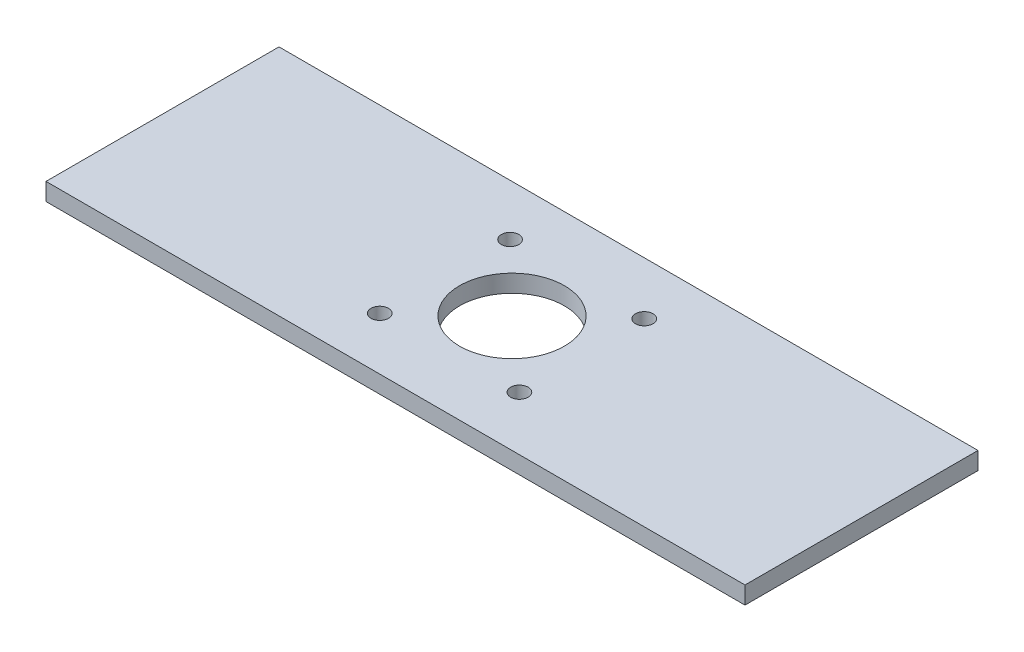
SolidWorks part; units mm, degrees
ref_plane "Front Plane" through (0, 0, 0) normal (0, 0, 1) x (1, 0, 0)
ref_plane "Top Plane" through (0, 0, 0) normal (0, 1, 0) x (1, 0, 0)
ref_plane "Right Plane" through (0, 0, 0) normal (1, 0, 0) x (0, 0, -1)
sketch "Sketch1" plane through (0, 0, 0) normal (0, 1, 0) x (1, 0, 0)
  line L1 (-95.25, -31.75) -> (95.25, -31.75)
  line L2 (-95.25, -31.75) -> (-95.25, 31.75)
  line L3 (-95.25, 31.75) -> (95.25, 31.75)
  line L4 (95.25, -31.75) -> (95.25, 31.75)
  line L5 (-95.25, -31.75) -> (95.25, 31.75) construction
  line L6 (-95.25, 31.75) -> (95.25, -31.75) construction
  point P0 (0, 0)
  dimension "D1" = 190.5
  dimension "D2" = 63.5
extrude "Boss-Extrude1" add sketch "Sketch1" along normal blind 4.7625
sketch "Sketch2" plane through (0, 4.7625, 0) normal (0, 1, 0) x (1, 0, 0)
  line L0 (-31.75, -31.75) -> (-31.75, 31.75)
  line L1 (-95.25, -31.75) -> (95.25, -31.75) construction
  line L2 (95.25, 31.75) -> (-95.25, 31.75) construction
  line L3 (-95.25, 31.75) -> (-95.25, -31.75) construction
  line L4 (31.75, 31.75) -> (31.75, -31.75)
  line L5 (95.25, -31.75) -> (95.25, 31.75) construction
  dimension "D1" = 63.5
  dimension "D2" = 63.5
sketch "Sketch3" plane through (0, 4.7625, 0) normal (0, 1, 0) x (1, 0, 0)
  circle A0 centre (0, 0) radius 14.2875
  dimension "D1" = 28.575
extrude "Cut-Extrude1" cut sketch "Sketch3" against normal through all
hole_wizard "3/16 (0.1875) Diameter Hole1" positions "Sketch4" profile "Sketch5" hole size "3/16" standard "ANSI Inch" end condition through all
sketch "Sketch4" plane through (0, 4.7625, 0) normal (0, 1, 0) x (1, 0, 0)
  point P0 (-18.2921, 17.7688)
  point P5 (-18.6293, -17.415)
  point P7 (18.6853, 17.3548)
  point P9 (19.0134, -16.9947)
  dimension "D1" = 25.5016
  dimension "D2" = 25.5016
  dimension "D3" = 25.5016
  dimension "D4" = 25.5016
sketch "Sketch5" plane through (-18.2921, 4.7625, -17.7688) normal (1, 0, 0) x (0, 0, 1)
  line L0 (0, 0) -> (0, 4.7625)
  line L1 (0, 4.7625) -> (2.3812, 4.7625)
  line L2 (2.3812, 4.7625) -> (2.3812, 0)
  line L5 (2.3812, 0) -> (0, 0)
  line L11 (0, -6.35) -> (0, 107.95) construction
  dimension "Thru Hole Dia." = 4.7625
  dimension "Thru Hole Depth" = 4.7625
